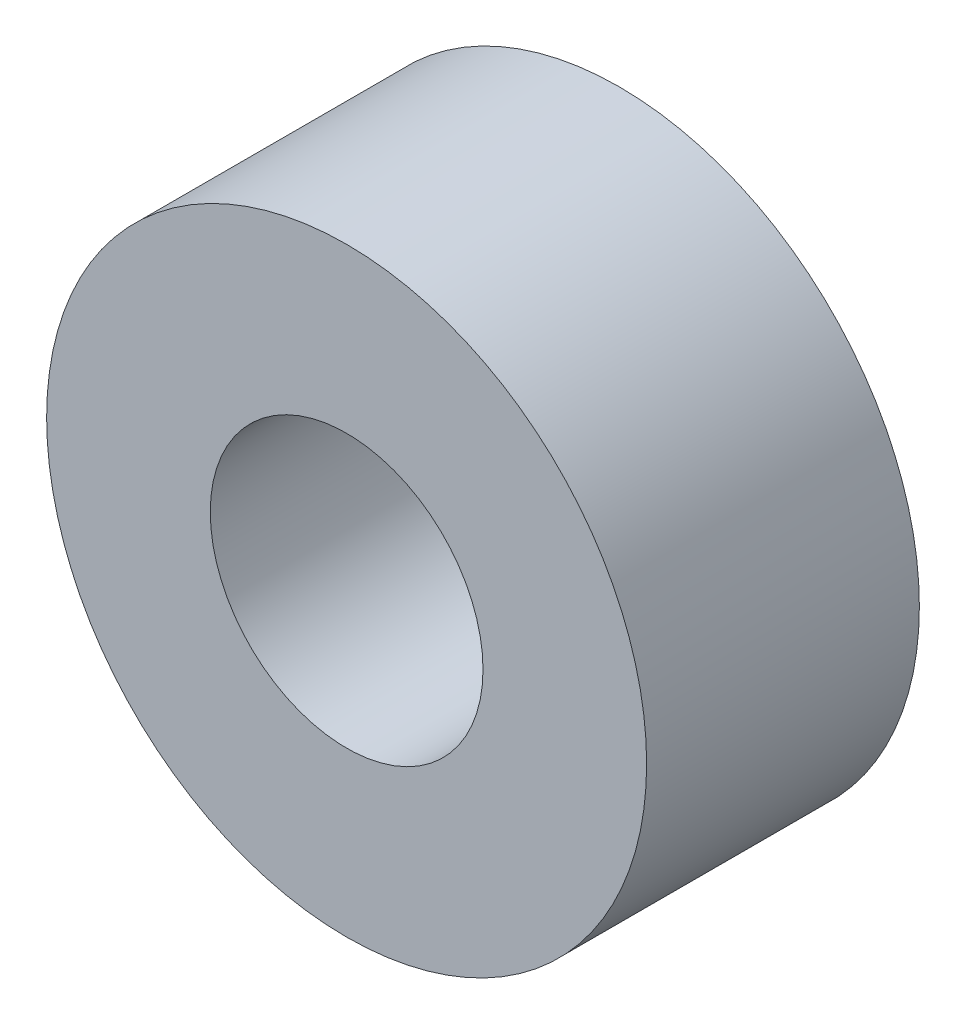
SolidWorks part; units mm, degrees
ref_plane "Plano frontal" through (0, 0, 0) normal (0, 0, 1) x (1, 0, 0)
ref_plane "Plano superior" through (0, 0, 0) normal (0, 1, 0) x (1, 0, 0)
ref_plane "Plano direito" through (0, 0, 0) normal (1, 0, 0) x (0, 0, -1)
sketch "Esboço1" plane through (0, 0, 0) normal (0, 0, 1) x (1, 0, 0)
  circle A0 centre (0, 0) radius 2.5
  circle A1 centre (0, 0) radius 5.5
  dimension "D1" = 5
  dimension "D2" = 11
extrude "Ressalto-extrusão1" add sketch "Esboço1" along normal blind 5
